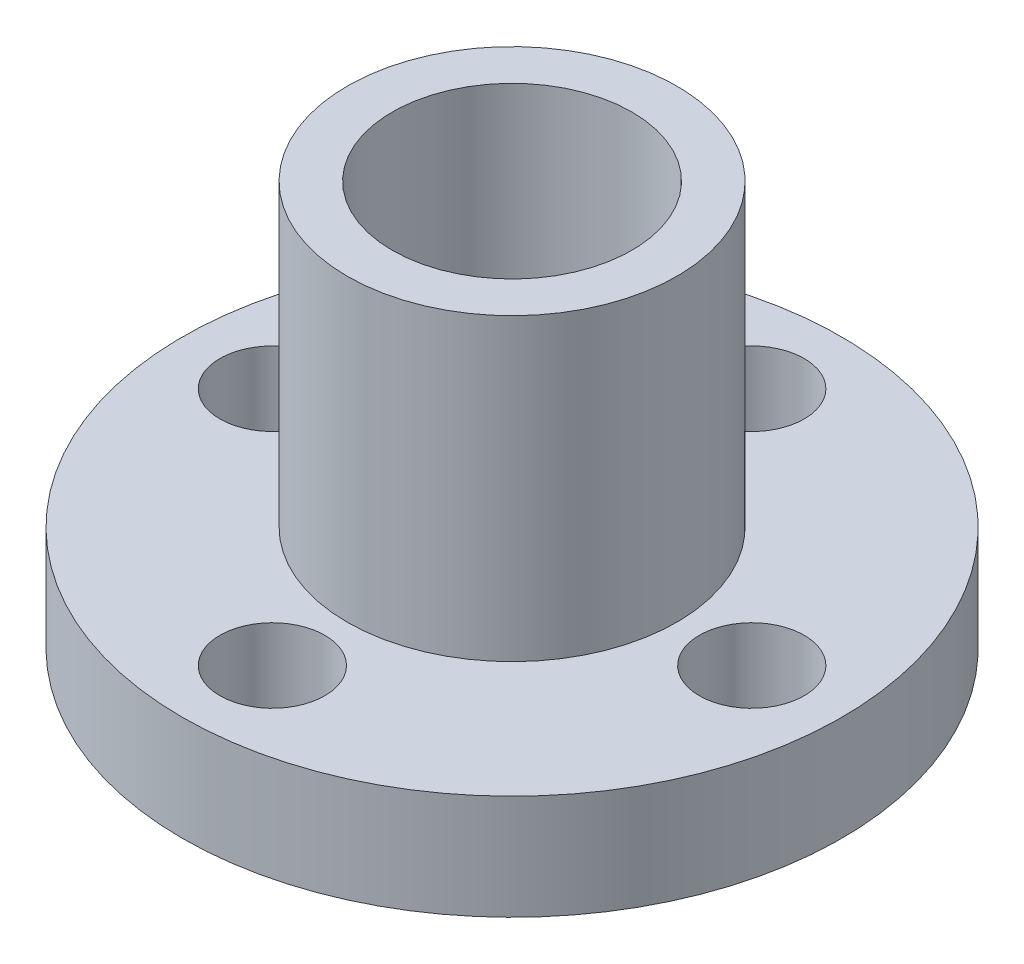
SolidWorks part; units mm, degrees
material "黄铜"
ref_plane "前视基准面" through (0, 0, 0) normal (0, 0, 1) x (1, 0, 0)
ref_plane "上视基准面" through (0, 0, 0) normal (0, 1, 0) x (1, 0, 0)
ref_plane "右视基准面" through (0, 0, 0) normal (1, 0, 0) x (0, 0, -1)
sketch "草图1" plane through (0, 0, 0) normal (0, 1, 0) x (1, 0, 0)
  circle A0 centre (0, 0) radius 5.5
  circle A1 centre (0, 0) radius 4
  dimension "D1" = 11
  dimension "D2" = 8
extrude "凸台-拉伸1" add sketch "草图1" along normal blind 1.5
sketch "草图2" plane through (0, 1.5, 0) normal (0, 1, 0) x (1, 0, 0)
  circle A0 centre (0, 0) radius 11
  circle A1 centre (0, 0) radius 4 construction
  circle A2 centre (0, 0) radius 4
  dimension "D1" = 22
extrude "凸台-拉伸2" add sketch "草图2" along normal blind 3.5
sketch "草图3" plane through (0, 5, 0) normal (0, 1, 0) x (1, 0, 0)
  circle A0 centre (0, 0) radius 5.5
  circle A1 centre (0, 0) radius 4 construction
  circle A2 centre (0, 0) radius 4
  dimension "D1" = 11
extrude "凸台-拉伸3" add sketch "草图3" along normal blind 10
sketch "草图4" plane through (0, 5, 0) normal (0, 1, 0) x (1, 0, 0)
  circle A0 centre (0, 0) radius 8 construction
  circle A1 centre (0, 8) radius 1.75
  circle A2 centre (8, 0) radius 1.75
  circle A3 centre (0, -8) radius 1.75
  circle A4 centre (-8, 0) radius 1.75
  point P13 (0, 0)
  dimension "D1" = 16
  dimension "D2" = 3.5
  dimension "D3" = 4
extrude "切除-拉伸1" cut sketch "草图4" against normal through all
